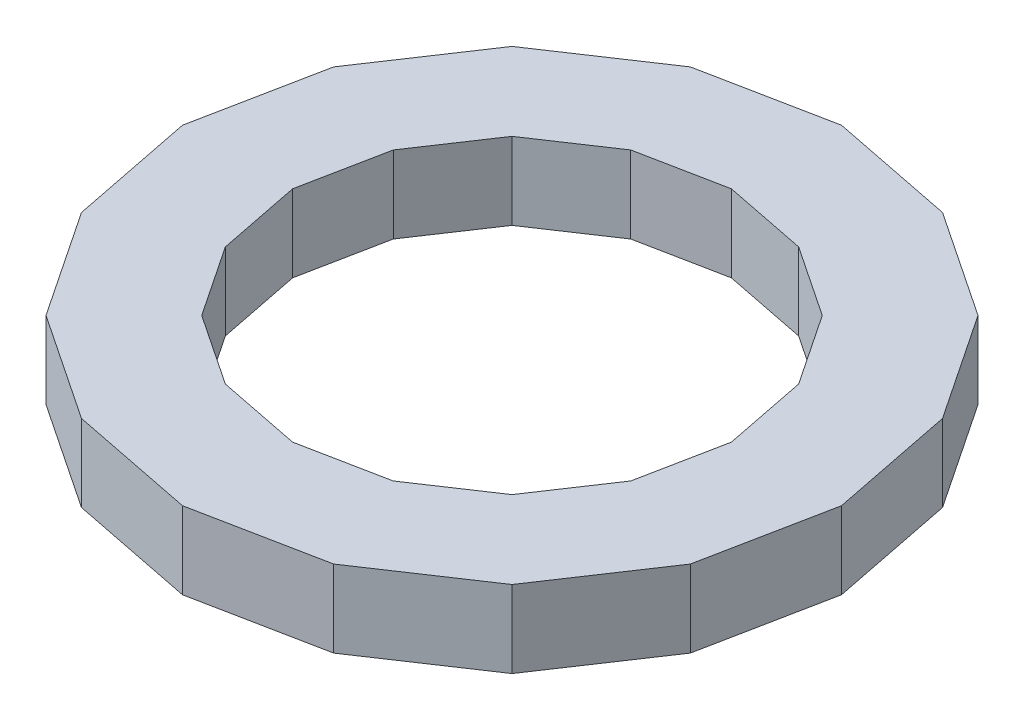
SolidWorks part; units mm, degrees
ref_plane "Front Plane" through (0, 0, 0) normal (0, 0, 1) x (1, 0, 0)
ref_plane "Top Plane" through (0, 0, 0) normal (0, 1, 0) x (1, 0, 0)
ref_plane "Right Plane" through (0, 0, 0) normal (1, 0, 0) x (0, 0, -1)
sketch "Sketch2" plane through (0, 0, 0) normal (0, 1, 0) x (1, 0, 0)
  line L0 (0, 0) -> (-54.1801, 0) construction
  line L1 (-81.3726, 0) -> (-75.1784, -31.1399)
  line L2 (-75.1784, -31.1399) -> (-57.5391, -57.5391)
  line L3 (-57.5391, -57.5391) -> (-31.1399, -75.1784)
  line L4 (-31.1399, -75.1784) -> (0, -81.3726)
  line L5 (0, -81.3726) -> (31.1399, -75.1784)
  line L6 (31.1399, -75.1784) -> (57.5391, -57.5391)
  line L7 (57.5391, -57.5391) -> (75.1784, -31.1399)
  line L8 (75.1784, -31.1399) -> (81.3726, 0)
  line L9 (81.3726, 0) -> (75.1784, 31.1399)
  line L10 (75.1784, 31.1399) -> (57.5391, 57.5391)
  line L11 (57.5391, 57.5391) -> (31.1399, 75.1784)
  line L12 (31.1399, 75.1784) -> (0, 81.3726)
  line L13 (0, 81.3726) -> (-31.1399, 75.1784)
  line L14 (-31.1399, 75.1784) -> (-57.5391, 57.5391)
  line L15 (-57.5391, 57.5391) -> (-75.1784, 31.1399)
  line L16 (-75.1784, 31.1399) -> (-81.3726, 0)
  line L17 (-54.1801, 0) -> (-50.0559, -20.7338)
  line L18 (-50.0559, -20.7338) -> (-38.3111, -38.3111)
  line L19 (-38.3111, -38.3111) -> (-20.7338, -50.0559)
  line L20 (-20.7338, -50.0559) -> (0, -54.1801)
  line L21 (0, -54.1801) -> (20.7338, -50.0559)
  line L22 (20.7338, -50.0559) -> (38.3111, -38.3111)
  line L23 (38.3111, -38.3111) -> (50.0559, -20.7338)
  line L24 (50.0559, -20.7338) -> (54.1801, 0)
  line L25 (54.1801, 0) -> (50.0559, 20.7338)
  line L26 (50.0559, 20.7338) -> (38.3111, 38.3111)
  line L27 (38.3111, 38.3111) -> (20.7338, 50.0559)
  line L28 (20.7338, 50.0559) -> (0, 54.1801)
  line L29 (0, 54.1801) -> (-20.7338, 50.0559)
  line L30 (-20.7338, 50.0559) -> (-38.3111, 38.3111)
  line L31 (-38.3111, 38.3111) -> (-50.0559, 20.7338)
  line L32 (-50.0559, 20.7338) -> (-54.1801, 0)
  line L33 (-81.3726, 0) -> (-54.1801, 0) construction
  circle A0 centre (0, 0) radius 79.809 construction
  circle A1 centre (0, 0) radius 53.139 construction
  dimension "D1" = 31.75
  dimension "D2" = 26.67
extrude "Boss-Extrude2" add sketch "Sketch2" along normal blind 19.05
